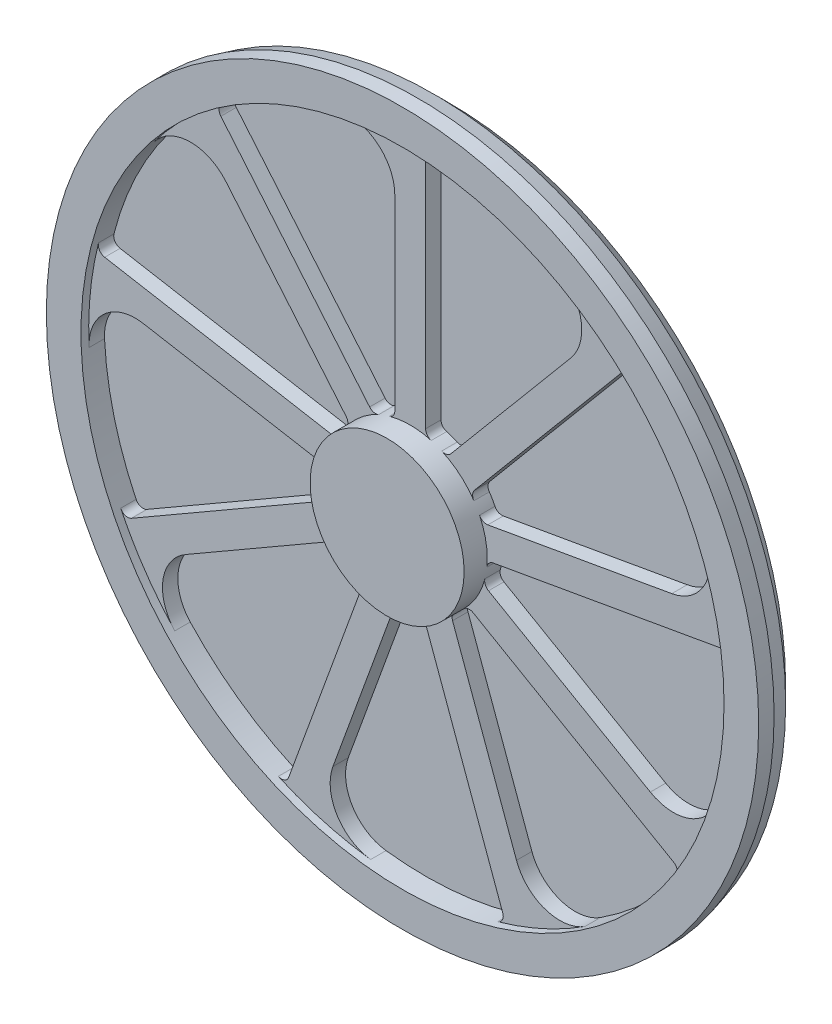
SolidWorks part; units mm, degrees
material "1060 Alloy"
ref_plane "Front Plane" through (0, 0, 0) normal (0, 0, 1) x (1, 0, 0)
ref_plane "Top Plane" through (0, 0, 0) normal (0, 1, 0) x (1, 0, 0)
ref_plane "Right Plane" through (0, 0, 0) normal (1, 0, 0) x (0, 0, -1)
sketch "Sketch1" plane through (0, 0, 0) normal (1, 0, 0) x (0, 0, -1)
  line L0 (-404.9793, 0) -> (404.9793, 0) construction
  line L1 (0, 0) -> (0, 100)
  line L2 (0, 100) -> (50, 100)
  line L3 (50, 100) -> (50, 417.5)
  line L4 (50, 417.5) -> (20, 417.5)
  line L5 (20, 417.5) -> (20, 462.5)
  line L6 (20, 462.5) -> (40, 462.5)
  line L7 (40, 462.5) -> (60.4904, 457.0096)
  line L8 (60.4904, 457.0096) -> (80, 437.5)
  line L9 (80, 437.5) -> (80, 0)
  line L10 (80, 0) -> (0, 0)
  point P9 (20, 440)
  point P14 (0, 0)
  dimension "D1" = 200
  dimension "D2" = 30
  dimension "D3" = 60
  dimension "D4" = 925
  dimension "D5" = 875
  dimension "D6" = 80
  dimension "D7" = 45
  dimension "D8" = 20
  dimension "D9" = 15
  dimension "D10" = 45
revolve "Revolve1" add sketch "Sketch1" angle 360 about L0
sketch "Sketch2" plane through (0, 0, -50) normal (0, 0, 1) x (1, 0, 0)
  line L0 (0, -640.2943) -> (0, 640.2943) construction
  line L1 (-20, 97.9796) -> (-20, 417.0207)
  line L2 (20, 97.9796) -> (20, 417.0207)
  circle A0 centre (0, 0) radius 417.5 construction
  arc A1 (20, 417.0207) -> (-20, 417.0207) centre (0, 0) ccw
  circle A2 centre (0, 0) radius 100 construction
  circle A3 centre (0, 0) radius 100 construction
  arc A4 (20, 97.9796) -> (-20, 97.9796) centre (0, 0) ccw
  dimension "D1" = 20
  dimension "D2" = 40
extrude "Boss-Extrude1" add sketch "Sketch2" along normal offset from surface (20 mm away) 10 up to face at (417.5, 0, -20)
fillet "Fillet1" radius 60 1 edges at (-20, 417.0207, -40)
fillet "Fillet2" radius 10 3 edges at (-20, 97.9796, -40) (20, 97.9796, -40) (20, 417.0207, -40)
pattern_circular "CirPattern1" count 9 over 360 about axis through (0, 0, 0) along (0, 0, 1) of "Fillet2", "Fillet1", "Boss-Extrude1"
equation "\"A\"= 60"
equation "\"B\"= 925"
equation "\"D3@Sketch1\"=\"A\""
equation "\"D4@Sketch1\"=\"B\""
equation "\"D5@Sketch1\"=\"B\"-50"
equation "\"D6@Sketch1\"=\"A\"+20"
